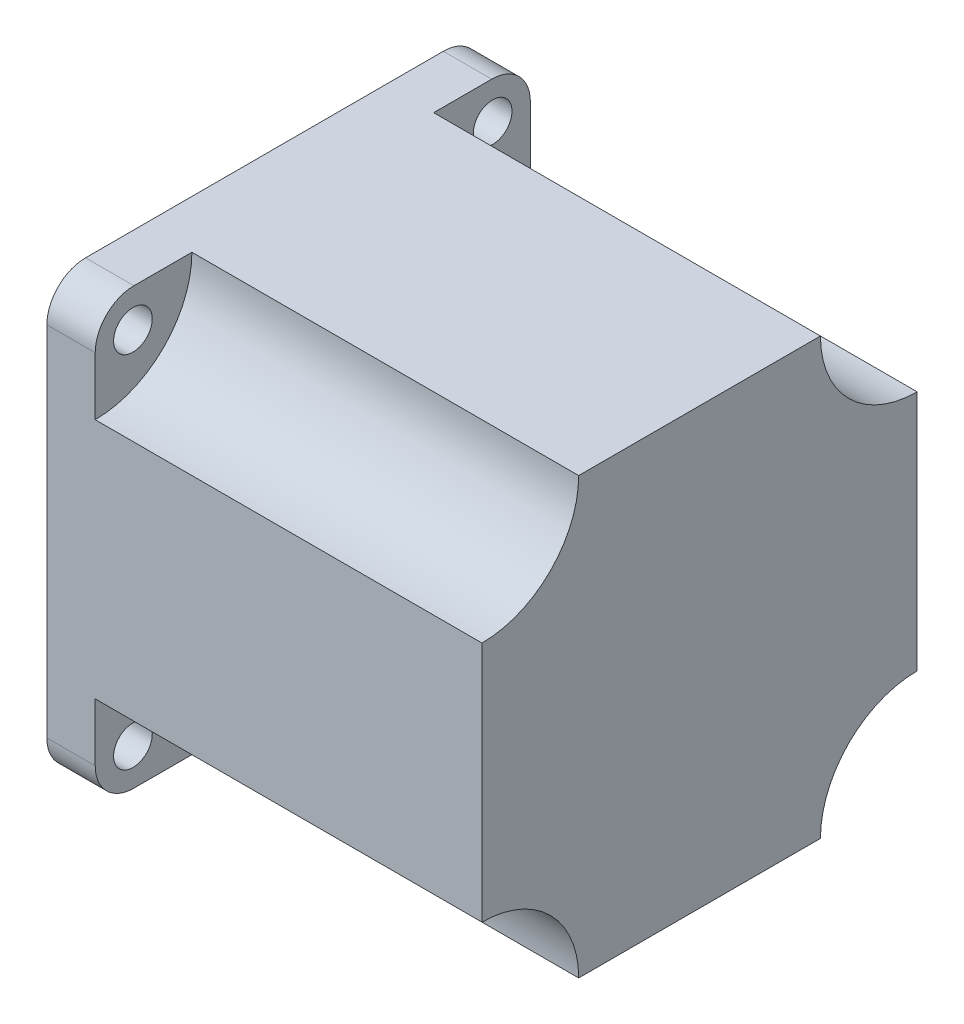
SolidWorks part; units mm, degrees
material "Plain Carbon Steel"
ref_plane "Front Plane" through (0, 0, 0) normal (0, 0, 1) x (1, 0, 0)
ref_plane "Top Plane" through (0, 0, 0) normal (0, 1, 0) x (1, 0, 0)
ref_plane "Right Plane" through (0, 0, 0) normal (1, 0, 0) x (0, 0, -1)
sketch "Sketch1" plane through (0, 0, 0) normal (1, 0, 0) x (0, 0, -1)
  line L0 (23.622, 23.622) -> (-23.622, 23.622) construction
  line L1 (28.575, 28.575) -> (-28.575, 28.575)
  line L2 (28.575, 28.575) -> (28.575, -28.575)
  line L3 (28.575, -28.575) -> (-28.575, -28.575)
  line L4 (-28.575, 28.575) -> (-28.575, -28.575)
  line L5 (28.575, 28.575) -> (-28.575, -28.575) construction
  line L6 (28.575, -28.575) -> (-28.575, 28.575) construction
  line L7 (-23.622, 23.622) -> (-23.622, -23.622) construction
  line L8 (-23.622, -23.622) -> (23.622, -23.622) construction
  line L9 (23.622, -23.622) -> (23.622, 23.622) construction
  circle A0 centre (23.622, 23.622) radius 2.54
  circle A1 centre (-23.622, 23.622) radius 2.54
  circle A2 centre (-23.622, -23.622) radius 2.54
  circle A3 centre (23.622, -23.622) radius 2.54
  point P0 (0, 0)
  dimension "D2" = 57.15
  dimension "D3" = 5.08
  dimension "D1" = 47.244
extrude "Boss-Extrude1" add sketch "Sketch1" along normal blind 6.35
fillet "Fillet1" radius 5.08 4 edges at (3.175, -28.575, -28.575) (3.175, -28.575, 28.575) (3.175, 28.575, -28.575) (3.175, 28.575, 28.575)
sketch "Sketch5" plane through (0, 0, 0) normal (-1, 0, 0) x (0, 0, 1)
  circle A0 centre (0, 0) radius 19.05
  dimension "D1" = 38.1
extrude "Boss-Extrude4" add sketch "Sketch5" along normal blind 1.524
sketch "Sketch6" plane through (-1.524, 0, 0) normal (-1, 0, 0) x (0, 0, 1)
  circle A0 centre (0, 0) radius 3.175
  dimension "D1" = 6.35
extrude "Boss-Extrude5" add sketch "Sketch6" along normal blind 19.05
sketch "Sketch7" plane through (6.35, 0, 0) normal (1, 0, 0) x (0, 0, -1)
  line L0 (-23.495, -28.575) -> (23.495, -28.575) construction
  line L1 (-28.575, 28.575) -> (28.575, 28.575) construction
  line L2 (-28.575, 28.575) -> (-28.575, -28.575) construction
  line L3 (-28.575, -28.575) -> (28.575, -28.575) construction
  line L4 (28.575, 28.575) -> (28.575, -28.575) construction
  line L5 (-28.575, 28.575) -> (28.575, -28.575) construction
  line L6 (-28.575, -28.575) -> (28.575, 28.575) construction
  line L7 (-28.575, 23.495) -> (-28.575, -23.495) construction
  line L8 (-15.875, 28.575) -> (15.875, 28.575)
  line L9 (28.575, 15.875) -> (28.575, -15.875)
  line L10 (15.875, -28.575) -> (-15.875, -28.575)
  line L11 (-28.575, -15.875) -> (-28.575, 15.875)
  arc A0 (-28.575, 15.875) -> (-15.875, 28.575) centre (-28.575, 28.575) ccw
  arc A1 (15.875, 28.575) -> (28.575, 15.875) centre (28.575, 28.575) ccw
  arc A2 (28.575, -15.875) -> (15.875, -28.575) centre (28.575, -28.575) ccw
  arc A3 (-15.875, -28.575) -> (-28.575, -15.875) centre (-28.575, -28.575) ccw
  point P0 (0, 0)
  dimension "D1" = 25.4
extrude "Boss-Extrude6" add sketch "Sketch7" along normal blind 50.8 contours A0 L8 A1 L9 A2 L10 A3 L11
